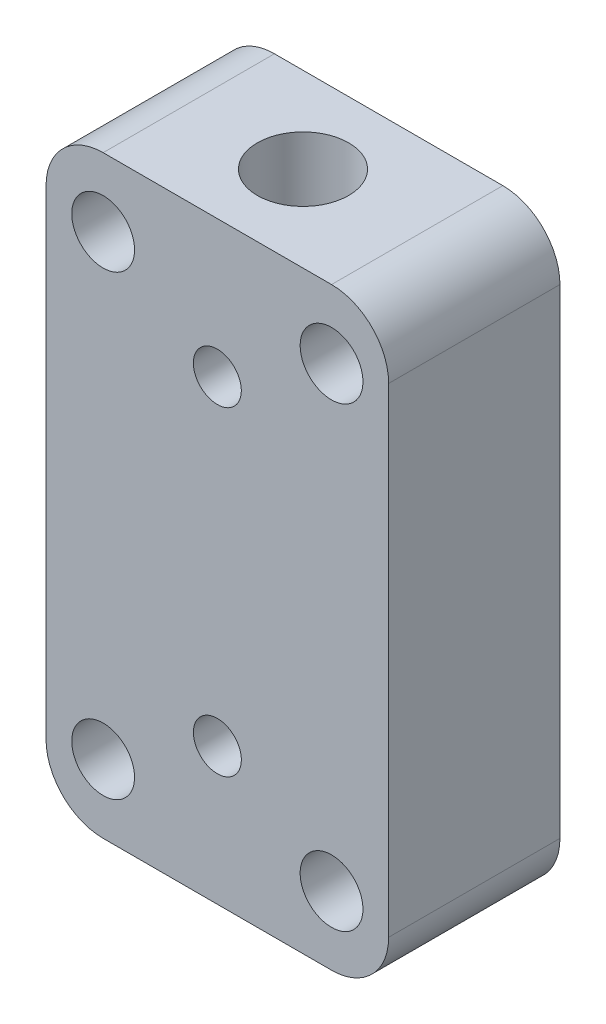
SolidWorks part; units mm, degrees
ref_plane "Plan de face" through (0, 0, 0) normal (0, 0, 1) x (1, 0, 0)
ref_plane "Plan de dessus" through (0, 0, 0) normal (0, 1, 0) x (1, 0, 0)
ref_plane "Plan de droite" through (0, 0, 0) normal (1, 0, 0) x (0, 0, -1)
sketch "Esquisse1" plane through (0, 0, 0) normal (0, 0, 1) x (1, 0, 0)
  line L1 (0, 0) -> (30, 0)
  line L2 (0, 0) -> (0, 52)
  line L3 (0, 52) -> (30, 52)
  line L4 (30, 0) -> (30, 52)
  dimension "D1" = 52
  dimension "D2" = 30
extrude "Boss.-Extru.1" add sketch "Esquisse1" along normal blind 15
sketch "Esquisse2" plane through (0, 52, 0) normal (0, 1, 0) x (1, 0, 0)
  line L0 (0, -7.5) -> (30, -7.5) construction
  line L1 (0, -15) -> (0, 0) construction
  line L2 (30, -15) -> (30, 0) construction
  circle A0 centre (15, -7.5) radius 4
  dimension "D1" = 8
extrude "Enlèv. mat.-Extru.1" cut sketch "Esquisse2" against normal through all both and the other way through all
sketch "Esquisse3" plane through (0, 0, 15) normal (0, 0, 1) x (1, 0, 0)
  line L0 (15, 0) -> (15, 52) construction
  line L1 (0, 0) -> (30, 0) construction
  line L2 (30, 52) -> (0, 52) construction
  line L3 (30, 26) -> (0, 26) construction
  line L4 (30, 0) -> (30, 52) construction
  line L5 (0, 52) -> (0, 0) construction
  circle A0 centre (5, 46) radius 2.75
  circle A1 centre (25, 46) radius 2.75
  circle A2 centre (25, 6) radius 2.75
  circle A3 centre (5, 6) radius 2.75
  dimension "D1" = 20
  dimension "D2" = 40
  dimension "D3" = 5.5
extrude "Enlèv. mat.-Extru.2" cut sketch "Esquisse3" against normal through all
fillet "Congé1" radius 5 4 edges at (30, 0, 7.5) (0, 0, 7.5) (0, 52, 7.5) (30, 52, 7.5)
sketch "Esquisse4" plane through (0, 0, 15) normal (0, 0, 1) x (1, 0, 0)
  line L0 (15, 0) -> (15, 52) construction
  line L1 (5, 0) -> (25, 0) construction
  line L2 (25, 52) -> (5, 52) construction
  line L3 (15, 26) -> (30, 26) construction
  line L4 (30, 5) -> (30, 47) construction
  circle A0 centre (15, 40) radius 2.1
  circle A1 centre (15, 12) radius 2.1
  dimension "D1" = 4.2
  dimension "D2" = 14
extrude "Enlèv. mat.-Extru.3" cut sketch "Esquisse4" against normal blind 10
